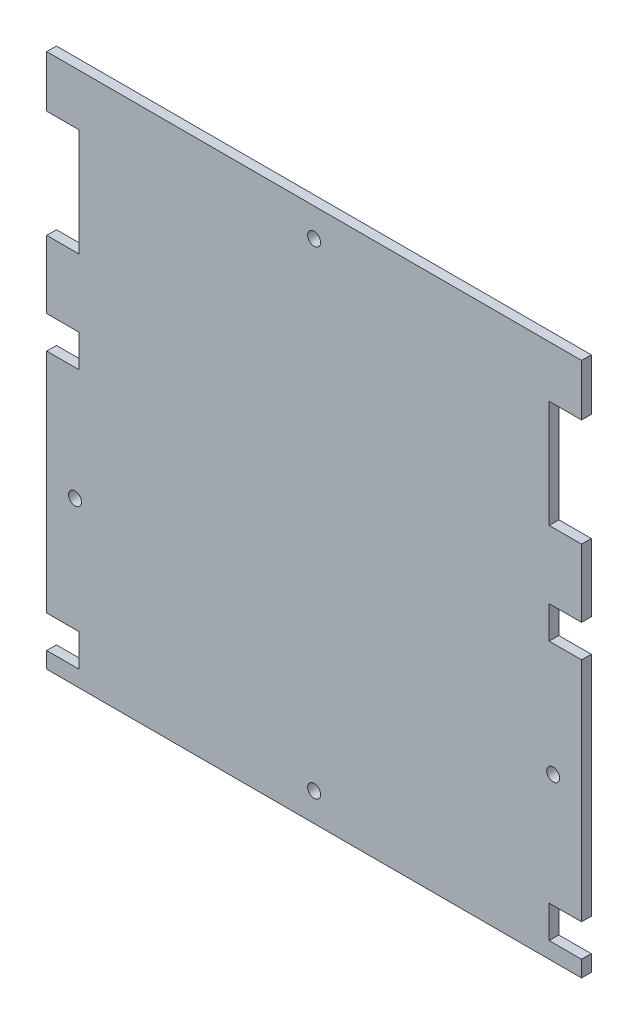
SolidWorks part; units mm, degrees
ref_plane "Plan de face" through (0, 0, 0) normal (0, 0, 1) x (1, 0, 0)
ref_plane "Plan de dessus" through (0, 0, 0) normal (0, 1, 0) x (1, 0, 0)
ref_plane "Plan de droite" through (0, 0, 0) normal (1, 0, 0) x (0, 0, -1)
sketch "Esquisse1" plane through (0, 0, 0) normal (0, 0, 1) x (1, 0, 0)
  line L0 (-89.7062, -247.5) -> (75.2938, -247.5)
  line L1 (75.2938, -247.5) -> (75.2938, -242.5)
  line L2 (75.2938, -242.5) -> (65.2938, -242.5)
  line L3 (65.2938, -242.5) -> (65.2938, -232.5)
  line L4 (65.2938, -232.5) -> (75.2938, -232.5)
  line L5 (75.2938, -232.5) -> (75.2938, -162.5)
  line L6 (75.2938, -162.5) -> (65.2938, -162.5)
  line L7 (65.2938, -162.5) -> (65.2938, -152.5)
  line L8 (65.2938, -152.5) -> (75.2938, -152.5)
  line L9 (75.2938, -152.5) -> (75.2938, -131.5831)
  line L10 (75.2938, -131.5831) -> (65.2938, -131.5831)
  line L11 (65.2938, -131.5831) -> (65.2938, -98.4169)
  line L12 (65.2938, -98.4169) -> (75.2938, -98.4169)
  line L13 (75.2938, -98.4169) -> (75.2938, -82.5)
  line L14 (75.2938, -82.5) -> (-89.7062, -82.5)
  line L15 (-89.7062, -82.5) -> (-89.7062, -98.4169)
  line L16 (-89.7062, -98.4169) -> (-79.7062, -98.4169)
  line L17 (-79.7062, -98.4169) -> (-79.7062, -131.5831)
  line L18 (-79.7062, -131.5831) -> (-89.7062, -131.5831)
  line L19 (-89.7062, -131.5831) -> (-89.7062, -152.5)
  line L20 (-89.7062, -152.5) -> (-79.7062, -152.5)
  line L21 (-79.7062, -152.5) -> (-79.7062, -162.5)
  line L22 (-79.7062, -162.5) -> (-89.7062, -162.5)
  line L23 (-89.7062, -162.5) -> (-89.7062, -232.5)
  line L24 (-89.7062, -232.5) -> (-79.7062, -232.5)
  line L25 (-79.7062, -232.5) -> (-79.7062, -242.5)
  line L26 (-79.7062, -242.5) -> (-89.7062, -242.5)
  line L27 (-89.7062, -242.5) -> (-89.7062, -247.5)
  circle A4 centre (-7.2062, -91.25) radius 2
  circle A5 centre (-80.9562, -197.5) radius 2
  circle A6 centre (-7.2062, -238.75) radius 2
  circle A7 centre (66.5438, -197.5) radius 2
extrude "Boss.-Extru.1" add sketch "Esquisse1" along normal blind 3
